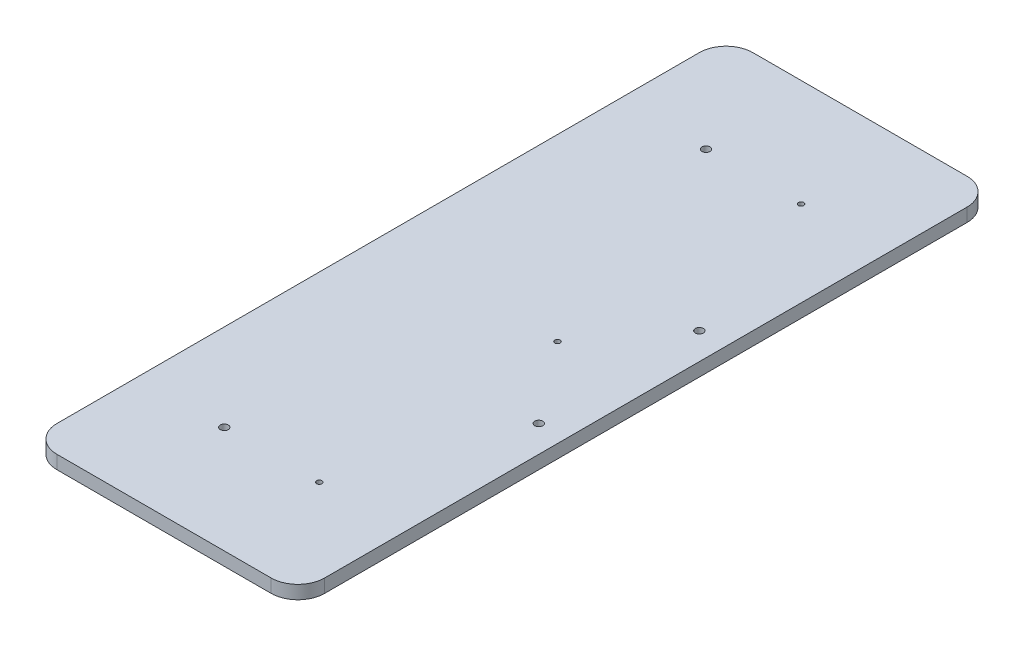
SolidWorks part; units mm, degrees
ref_plane "前视基准面" through (0, 0, 0) normal (0, 0, 1) x (1, 0, 0)
ref_plane "上视基准面" through (0, 0, 0) normal (0, 1, 0) x (1, 0, 0)
ref_plane "右视基准面" through (0, 0, 0) normal (1, 0, 0) x (0, 0, -1)
sketch "草图1" plane through (0, 0, 0) normal (0, 1, 0) x (1, 0, 0)
  line L1 (-150, 100) -> (150, 100)
  line L2 (-150, 100) -> (-150, -100)
  line L3 (-150, -100) -> (150, -100)
  line L4 (150, 100) -> (150, -100)
  line L5 (-150, 100) -> (150, -100) construction
  line L6 (-150, -100) -> (150, 100) construction
  point P0 (0, 0)
  dimension "D1" = 200
  dimension "D2" = 300
extrude "凸台-拉伸1" add sketch "草图1" along normal blind 5
sketch "草图5" plane through (0, 5, 0) normal (0, 1, 0) x (1, 0, 0)
  line L0 (150, 100) -> (-150, 100) construction
  line L2 (50, 100) -> (50, -100)
  line L4 (150, 100) -> (150, -100)
  line L7 (50, 100) -> (50, 130)
  line L8 (50, 130) -> (150, 130)
  line L9 (150, 100) -> (150, 130)
  line L11 (50, -100) -> (50, -130)
  line L12 (50, -130) -> (150, -130)
  line L13 (150, -100) -> (150, -130)
  dimension "D1" = 100
  dimension "D2" = 30
  dimension "D3" = 30
extrude "凸台-拉伸2" add sketch "草图5" against normal up to surface (5 mm away) up to face at (0, 0, 0)
sketch "草图6" plane through (0, 5, 0) normal (0, 1, 0) x (1, 0, 0)
  line L0 (-150, 100) -> (50, 100)
  line L1 (50, 100) -> (50, -100)
  line L2 (50, -100) -> (-150, -100)
  line L3 (-150, -100) -> (-150, 100)
extrude "切除-拉伸4" cut sketch "草图6" against normal blind 35
sketch "草图7" plane through (0, 5, 0) normal (0, 1, 0) x (1, 0, 0)
  line L0 (142.5, -64.8472) -> (142.5, -158.6011)
  line L1 (142.5, 85) -> (142.5, -85) construction
  line L2 (142.5, -158.6011) -> (197.1946, -158.6011)
  line L3 (197.1946, -158.6011) -> (197.1946, 177.5566)
  line L4 (197.1946, 177.5566) -> (142.5, 177.5566)
  line L5 (142.5, 177.5566) -> (142.5, -64.8472)
extrude "切除-拉伸5" cut sketch "草图7" against normal blind 50
sketch "草图8" plane through (0, 5, 0) normal (0, 1, 0) x (1, 0, 0)
  line L1 (142.5, 130) -> (42.5, 130)
  line L2 (142.5, 130) -> (142.5, -130)
  line L3 (142.5, -130) -> (42.5, -130)
  line L4 (42.5, 130) -> (42.5, -130)
  dimension "D1" = 100
extrude "凸台-拉伸3" add sketch "草图8" against normal blind 5
sketch "草图9" plane through (0, 5, 0) normal (0, 1, 0) x (1, 0, 0)
  circle A0 centre (132.5, 30) radius 1.5
  circle A1 centre (132.5, -30) radius 1.5
extrude "切除-拉伸6" cut sketch "草图9" against normal blind 15
sketch "草图10" plane through (0, 5, 0) normal (0, 1, 0) x (1, 0, 0)
  circle A0 centre (75, 90) radius 1.5
  circle A2 centre (75, -90) radius 1.5
extrude "切除-拉伸7" cut sketch "草图10" against normal blind 15
sketch "草图11" plane through (0, 5, 0) normal (0, 1, 0) x (1, 0, 0)
  circle A0 centre (110.5, 90) radius 1
  circle A1 centre (109.5, 0) radius 1
  circle A2 centre (110.5, -90) radius 1
extrude "切除-拉伸8" cut sketch "草图11" against normal blind 10
fillet "圆角5" radius 10 4 edges at (42.5, 2.5, 130) (142.5, 2.5, 130) (142.5, 2.5, -130) (42.5, 2.5, -130)
